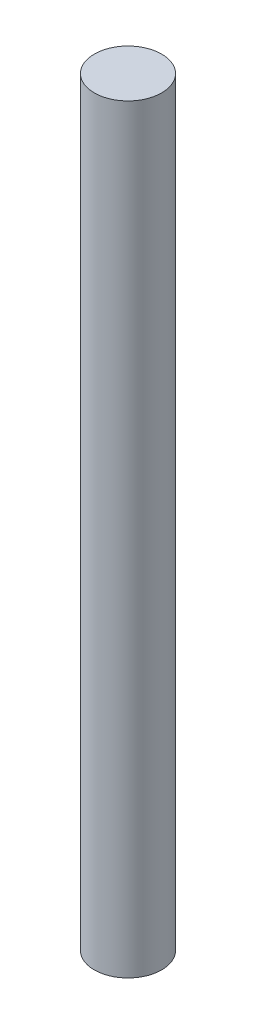
SolidWorks part; units mm, degrees
ref_plane "Front Plane" through (0, 0, 0) normal (0, 0, 1) x (1, 0, 0)
ref_plane "Top Plane" through (0, 0, 0) normal (0, 1, 0) x (1, 0, 0)
ref_plane "Right Plane" through (0, 0, 0) normal (1, 0, 0) x (0, 0, -1)
sketch "Sketch2" plane through (0, 0, 0) normal (0, 1, 0) x (1, 0, 0)
  circle A0 centre (0, 0) radius 3.9
  dimension "D1" = 7.8
extrude "Boss-Extrude1" add sketch "Sketch2" along normal blind 88
